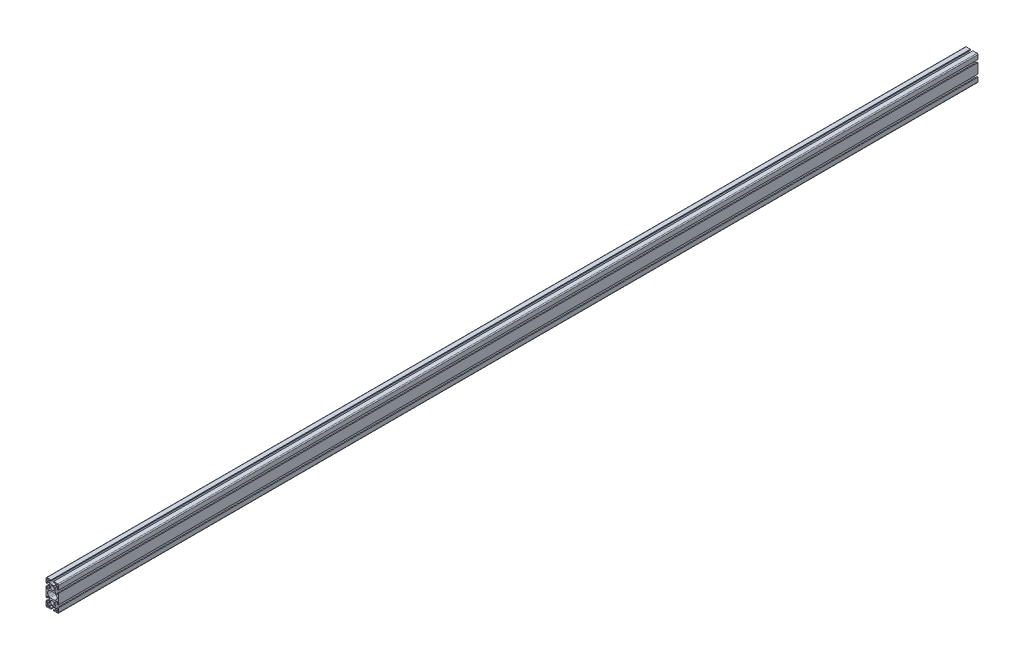
SolidWorks part; units mm, degrees
ref_plane "Front Plane" through (0, 0, 0) normal (0, 0, 1) x (1, 0, 0)
ref_plane "Top Plane" through (0, 0, 0) normal (0, 1, 0) x (1, 0, 0)
ref_plane "Right Plane" through (0, 0, 0) normal (1, 0, 0) x (0, 0, -1)
sketch "Sketch1" plane through (0, 0, 0) normal (0, 0, 1) x (1, 0, 0)
  line L0 (-17, -40) -> (-4.1, -40)
  line L1 (-4.1, -40) -> (-4.1, -37)
  line L2 (-4.1, -37) -> (-10.5, -37)
  line L3 (-10.5, -37) -> (-10.5, -33.6627)
  line L4 (-10.0314, -32.5314) -> (-7.4645, -29.9645)
  line L5 (-3.9289, -28.5) -> (3.9289, -28.5)
  line L6 (7.4645, -29.9645) -> (10.0314, -32.5314)
  line L7 (10.5, -33.6627) -> (10.5, -37)
  line L8 (10.5, -37) -> (4.1, -37)
  line L9 (4.1, -37) -> (4.1, -40)
  line L10 (4.1, -40) -> (17, -40)
  line L11 (20, -37) -> (20, -24.1)
  line L12 (20, -24.1) -> (17, -24.1)
  line L13 (17, -24.1) -> (17, -30.5)
  line L14 (17, -30.5) -> (13.6627, -30.5)
  line L15 (12.5314, -30.0314) -> (9.9645, -27.4645)
  line L16 (8.5, -23.9289) -> (8.5, -16.0711)
  line L17 (9.9645, -12.5355) -> (12.5314, -9.9686)
  line L18 (13.6627, -9.5) -> (17, -9.5)
  line L19 (17, -9.5) -> (17, -15.9)
  line L20 (17, -15.9) -> (20, -15.9)
  line L21 (20, -15.9) -> (20, 15.9)
  line L22 (20, 15.9) -> (17, 15.9)
  line L23 (17, 15.9) -> (17, 9.5)
  line L24 (17, 9.5) -> (13.6627, 9.5)
  line L25 (12.5314, 9.9686) -> (9.9645, 12.5355)
  line L26 (8.5, 16.0711) -> (8.5, 23.9289)
  line L27 (9.9645, 27.4645) -> (12.5314, 30.0314)
  line L28 (13.6627, 30.5) -> (17, 30.5)
  line L29 (17, 30.5) -> (17, 24.1)
  line L30 (17, 24.1) -> (20, 24.1)
  line L31 (20, 24.1) -> (20, 37)
  line L32 (17, 40) -> (4.1, 40)
  line L33 (4.1, 40) -> (4.1, 37)
  line L34 (4.1, 37) -> (10.5, 37)
  line L35 (10.5, 37) -> (10.5, 33.6627)
  line L36 (10.0314, 32.5314) -> (7.4645, 29.9645)
  line L37 (3.9289, 28.5) -> (-3.9289, 28.5)
  line L38 (-7.4645, 29.9645) -> (-10.0314, 32.5314)
  line L39 (-10.5, 33.6627) -> (-10.5, 37)
  line L40 (-10.5, 37) -> (-4.1, 37)
  line L41 (-4.1, 37) -> (-4.1, 40)
  line L42 (-4.1, 40) -> (-17, 40)
  line L43 (-20, 37) -> (-20, 24.1)
  line L44 (-20, 24.1) -> (-17, 24.1)
  line L45 (-17, 24.1) -> (-17, 30.5)
  line L46 (-17, 30.5) -> (-13.6627, 30.5)
  line L47 (-12.5314, 30.0314) -> (-9.9645, 27.4645)
  line L48 (-8.5, 23.9289) -> (-8.5, 16.0711)
  line L49 (-9.9645, 12.5355) -> (-12.5314, 9.9686)
  line L50 (-13.6627, 9.5) -> (-17, 9.5)
  line L51 (-17, 9.5) -> (-17, 15.9)
  line L52 (-17, 15.9) -> (-20, 15.9)
  line L53 (-20, 15.9) -> (-20, -15.9)
  line L54 (-20, -15.9) -> (-17, -15.9)
  line L55 (-17, -15.9) -> (-17, -9.5)
  line L56 (-17, -9.5) -> (-13.6627, -9.5)
  line L57 (-12.5314, -9.9686) -> (-9.9645, -12.5355)
  line L58 (-8.5, -16.0711) -> (-8.5, -23.9289)
  line L59 (-9.9645, -27.4645) -> (-12.5314, -30.0314)
  line L60 (-13.6627, -30.5) -> (-17, -30.5)
  line L61 (-17, -30.5) -> (-17, -24.1)
  line L62 (-17, -24.1) -> (-20, -24.1)
  line L63 (-20, -24.1) -> (-20, -37)
  line L64 (-14.2426, -4.2426) -> (-9.9497, -8.5355)
  line L65 (-6.4142, -10) -> (6.4142, -10)
  line L66 (9.9497, -8.5355) -> (14.2426, -4.2426)
  line L67 (14.2426, 4.2426) -> (9.9497, 8.5355)
  line L68 (6.4142, 10) -> (-6.4142, 10)
  line L69 (-9.9497, 8.5355) -> (-14.2426, 4.2426)
  arc A0 (-20, -37) -> (-17, -40) centre (-17, -37) ccw
  arc A1 (-10.5, -33.6627) -> (-10.0314, -32.5314) centre (-8.9, -33.6627) cw
  arc A2 (-7.4645, -29.9645) -> (-3.9289, -28.5) centre (-3.9289, -33.5) cw
  arc A3 (3.9289, -28.5) -> (7.4645, -29.9645) centre (3.9289, -33.5) cw
  arc A4 (10.0314, -32.5314) -> (10.5, -33.6627) centre (8.9, -33.6627) cw
  arc A5 (17, -40) -> (20, -37) centre (17, -37) ccw
  arc A6 (13.6627, -30.5) -> (12.5314, -30.0314) centre (13.6627, -28.9) cw
  arc A7 (9.9645, -27.4645) -> (8.5, -23.9289) centre (13.5, -23.9289) cw
  arc A8 (8.5, -16.0711) -> (9.9645, -12.5355) centre (13.5, -16.0711) cw
  arc A9 (12.5314, -9.9686) -> (13.6627, -9.5) centre (13.6627, -11.1) cw
  arc A10 (13.6627, 9.5) -> (12.5314, 9.9686) centre (13.6627, 11.1) cw
  arc A11 (9.9645, 12.5355) -> (8.5, 16.0711) centre (13.5, 16.0711) cw
  arc A12 (8.5, 23.9289) -> (9.9645, 27.4645) centre (13.5, 23.9289) cw
  arc A13 (12.5314, 30.0314) -> (13.6627, 30.5) centre (13.6627, 28.9) cw
  arc A14 (20, 37) -> (17, 40) centre (17, 37) ccw
  arc A15 (10.5, 33.6627) -> (10.0314, 32.5314) centre (8.9, 33.6627) cw
  arc A16 (7.4645, 29.9645) -> (3.9289, 28.5) centre (3.9289, 33.5) cw
  arc A17 (-3.9289, 28.5) -> (-7.4645, 29.9645) centre (-3.9289, 33.5) cw
  arc A18 (-10.0314, 32.5314) -> (-10.5, 33.6627) centre (-8.9, 33.6627) cw
  arc A19 (-17, 40) -> (-20, 37) centre (-17, 37) ccw
  arc A20 (-13.6627, 30.5) -> (-12.5314, 30.0314) centre (-13.6627, 28.9) cw
  arc A21 (-9.9645, 27.4645) -> (-8.5, 23.9289) centre (-13.5, 23.9289) cw
  arc A22 (-8.5, 16.0711) -> (-9.9645, 12.5355) centre (-13.5, 16.0711) cw
  arc A23 (-12.5314, 9.9686) -> (-13.6627, 9.5) centre (-13.6627, 11.1) cw
  arc A24 (-13.6627, -9.5) -> (-12.5314, -9.9686) centre (-13.6627, -11.1) cw
  arc A25 (-9.9645, -12.5355) -> (-8.5, -16.0711) centre (-13.5, -16.0711) cw
  arc A26 (-8.5, -23.9289) -> (-9.9645, -27.4645) centre (-13.5, -23.9289) cw
  arc A27 (-12.5314, -30.0314) -> (-13.6627, -30.5) centre (-13.6627, -28.9) cw
  circle A28 centre (15, 35) radius 2.5
  circle A29 centre (15, -35) radius 2.5
  circle A30 centre (0, 20) radius 6
  circle A31 centre (0, -20) radius 6
  arc A32 (-14.2426, 4.2426) -> (-14.2426, -4.2426) centre (-10, 0) ccw
  arc A33 (-9.9497, -8.5355) -> (-6.4142, -10) centre (-6.4142, -5) ccw
  arc A34 (6.4142, -10) -> (9.9497, -8.5355) centre (6.4142, -5) ccw
  arc A35 (14.2426, -4.2426) -> (14.2426, 4.2426) centre (10, 0) ccw
  arc A36 (9.9497, 8.5355) -> (6.4142, 10) centre (6.4142, 5) ccw
  arc A37 (-6.4142, 10) -> (-9.9497, 8.5355) centre (-6.4142, 5) ccw
  circle A38 centre (-15, 35) radius 2.5
  circle A39 centre (-15, -35) radius 2.5
  dimension "D1" = 40
  dimension "D2" = 80
extrude "Boss-Extrude1" add sketch "Sketch1" against normal blind 2900
